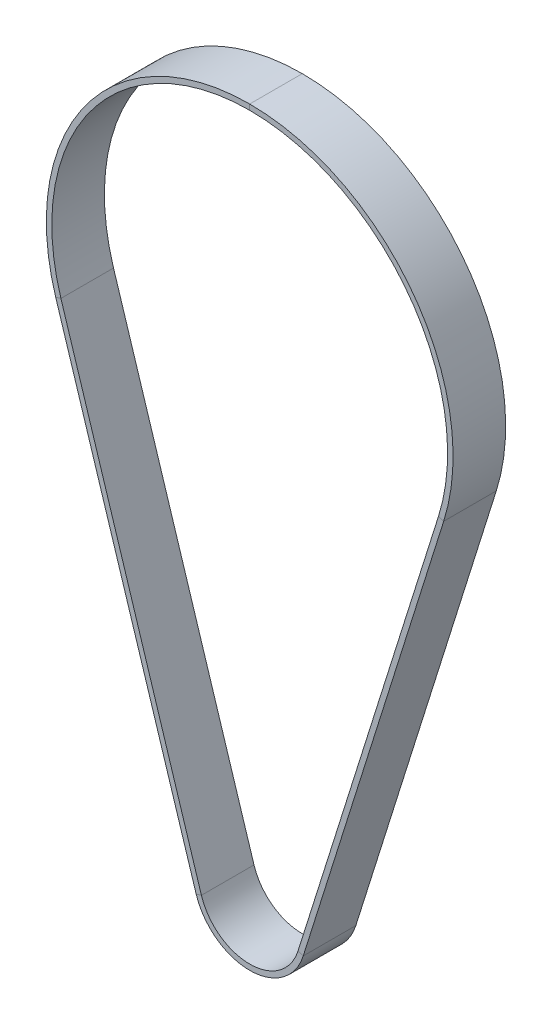
SolidWorks part; units mm, degrees
ref_plane "Спереди" through (0, 0, 0) normal (0, 0, 1) x (1, 0, 0)
ref_plane "Сверху" through (0, 0, 0) normal (0, 1, 0) x (1, 0, 0)
ref_plane "Справа" through (0, 0, 0) normal (1, 0, 0) x (0, 0, -1)
other "Configuration Table"
sketch "Эскиз1" plane through (0, 0, 0) normal (0, 0, 1) x (1, 0, 0)
  line L0 (-55.3285, -17.4) -> (-15.263, -144.8)
  line L2 (15.263, -144.8) -> (55.3285, -17.4)
  arc A0 (55.3285, -17.4) -> (-55.3285, -17.4) centre (0, 0) ccw
  arc A1 (-15.263, -144.8) -> (15.263, -144.8) centre (0, -140) ccw
  dimension "D1" = 116
  dimension "D2" = 32
  dimension "D3" = 140
sketch "Эскиз2" plane through (0, 0, 0) normal (1, 0, 0) x (0, 0, -1)
  line L0 (0, 58) -> (0, -17.4) construction
  line L1 (-15, 58) -> (0, 58)
  line L2 (-15, 58) -> (-15, 56.44)
  line L3 (-15, 56.44) -> (0, 56.44)
  line L4 (0, 58) -> (0, 56.44)
  dimension "D1" = 1.56
  dimension "D2" = 15
  dimension "D3" = 58
sweep "По траектории1" add profiles "Эскиз2" path "Эскиз1"
